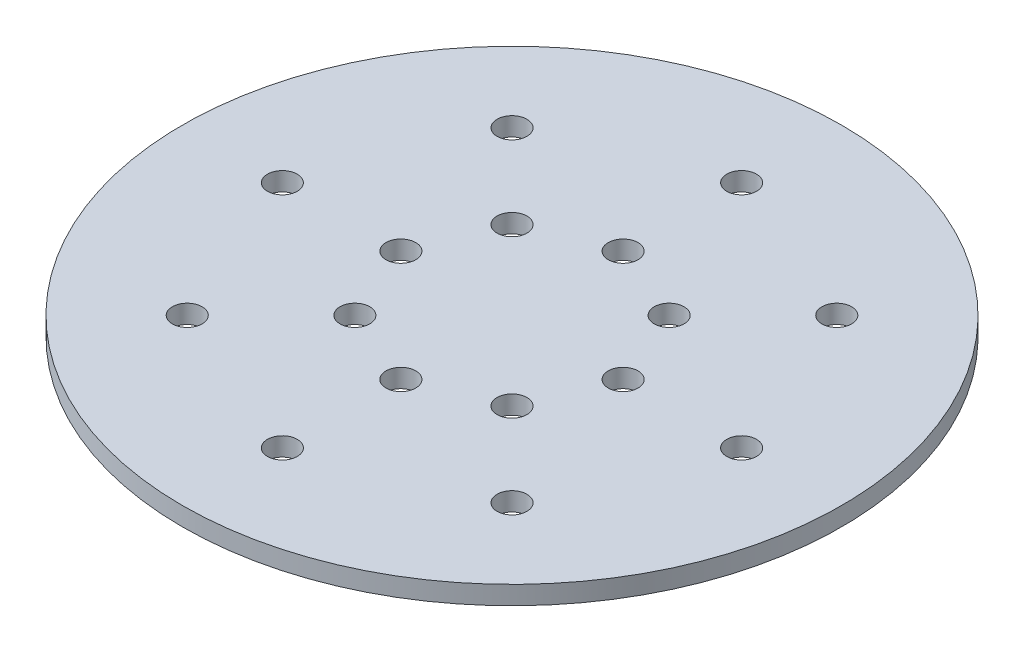
SolidWorks part; units mm, degrees
material "6061 Alloy"
ref_plane "Front Plane" through (0, 0, 0) normal (0, 0, 1) x (1, 0, 0)
ref_plane "Top Plane" through (0, 0, 0) normal (0, 1, 0) x (1, 0, 0)
ref_plane "Right Plane" through (0, 0, 0) normal (1, 0, 0) x (0, 0, -1)
sketch "Sketch1" plane through (0, 0, 0) normal (0, 1, 0) x (1, 0, 0)
  circle A0 centre (0, 0) radius 56.5
  circle A1 centre (0, 19.05) radius 2.5527
  circle A2 centre (13.4704, 13.4704) radius 2.5527
  circle A3 centre (19.05, 0) radius 2.5527
  circle A4 centre (13.4704, -13.4704) radius 2.5527
  circle A5 centre (0, -19.05) radius 2.5527
  circle A6 centre (-13.4704, -13.4704) radius 2.5527
  circle A7 centre (-19.05, 0) radius 2.5527
  circle A8 centre (-13.4704, 13.4704) radius 2.5527
  circle A9 centre (0, 0) radius 44.45 construction
  circle A10 centre (0, 0) radius 25.4 construction
  point P6 (0, 39.37)
  point P21 (0, 0)
  point P23 (27.8388, 27.8388)
  point P24 (0, 0)
  point P25 (0, 0)
  point P26 (39.37, 0)
  point P27 (27.8388, -27.8388)
  point P28 (0, -39.37)
  point P29 (-27.8388, -27.8388)
  point P30 (-39.37, 0)
  point P31 (-27.8388, 27.8388)
  point P32 (0, 0)
  dimension "D2" = 5.1054
  dimension "D4" = 113
  dimension "D6" = 50.8
  dimension "D7" = 88.9
  dimension "D1" = 19.05
  dimension "D5" = 39.37
  dimension "D3" = 8
  dimension "D8" = 8
extrude "Boss-Extrude1" add sketch "Sketch1" along normal blind 3.175 contours A1 | A2 | A0 A8 A7 A6 A5 A4 A3 A2 A1 | A3 | A4 | A5 | A6 | A8 | A7
hole_wizard "1/4-20 Tapped Hole1" positions "3DSketch1" profile "Sketch2" tap size "1/4-20" standard "ANSI Inch" end condition through all
sketch3d "3DSketch1"
  point P47 (13.4704, 0, -13.4704)
  point P49 (19.05, 0, 0)
  point P51 (13.4704, 0, 13.4704)
  point P53 (0, 0, 19.05)
  point P55 (-13.4704, 0, 13.4704)
  point P57 (-19.05, 0, 0)
  point P59 (-13.4704, 0, -13.4704)
  point P89 (0, 0, -19.05)
  point P93 (0, 0, -39.37)
  point P95 (-27.8388, 0, -27.8388)
  point P97 (-39.37, 0, 0)
  point P100 (-27.8388, 0, 27.8388)
  point P102 (0, 0, 39.37)
  point P104 (27.8388, 0, 27.8388)
  point P106 (39.37, 0, 0)
  point P108 (27.8388, 0, -27.8388)
  point P115 (0, 0, 0)
  point P117 (0, 0, 0)
  point P119 (0, 0, 0)
  point P121 (0, 0, 0)
sketch "Sketch2" plane through (13.4704, 0, -13.4704) normal (1, 0, 0) x (0, 0, -1)
  line L0 (0, 0) -> (0, 3.175)
  line L1 (0, 3.175) -> (2.5527, 3.175)
  line L2 (2.5527, 3.175) -> (2.5527, 0)
  line L5 (2.5527, 0) -> (0, 0)
  line L11 (0, -6.35) -> (0, 107.95) construction
  dimension "Thru Tap Drill Dia." = 5.1054
  dimension "Thru Tap Drill Depth" = 3.175
cosmetic thread "Hole Thread2" parameters "D2"=6.35
cosmetic thread "Hole Thread3" parameters "D2"=6.35
cosmetic thread "Hole Thread4" parameters "D2"=6.35
cosmetic thread "Hole Thread5" parameters "D2"=6.35
cosmetic thread "Hole Thread6" parameters "D2"=6.35
cosmetic thread "Hole Thread7" parameters "D2"=6.35
cosmetic thread "Hole Thread8" parameters "D2"=6.35
cosmetic thread "Hole Thread9" parameters "D2"=6.35
cosmetic thread "Hole Thread10" parameters "D2"=6.35
cosmetic thread "Hole Thread11" parameters "D2"=6.35
cosmetic thread "Hole Thread12" parameters "D2"=6.35
cosmetic thread "Hole Thread13" parameters "D2"=6.35
cosmetic thread "Hole Thread14" parameters "D2"=6.35
cosmetic thread "Hole Thread15" parameters "D2"=6.35
cosmetic thread "Hole Thread16" parameters "D2"=6.35
cosmetic thread "Hole Thread17" parameters "D2"=6.35
